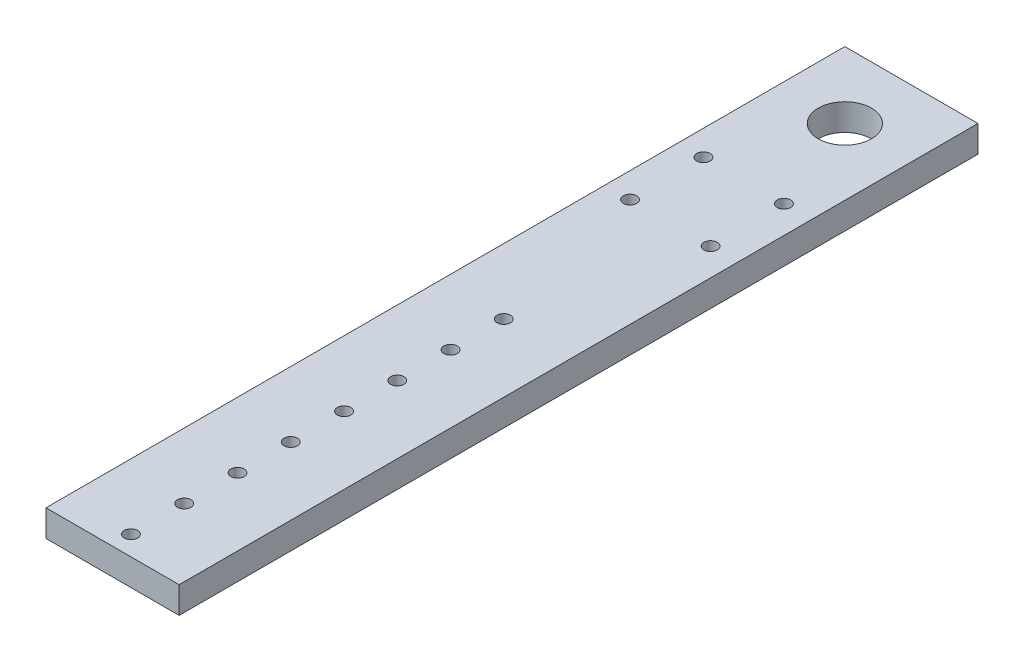
SolidWorks part; units mm, degrees
ref_plane "Front Plane" through (0, 0, 0) normal (0, 0, 1) x (1, 0, 0)
ref_plane "Top Plane" through (0, 0, 0) normal (0, 1, 0) x (1, 0, 0)
ref_plane "Right Plane" through (0, 0, 0) normal (1, 0, 0) x (0, 0, -1)
sketch "Sketch1" plane through (0, 0, 0) normal (0, 1, 0) x (1, 0, 0)
  line L1 (0, 0) -> (-127, 0)
  line L2 (0, 0) -> (0, 762)
  line L3 (0, 762) -> (-127, 762)
  line L4 (-127, 0) -> (-127, 762)
  point P7 (-52.4485, 452.4901)
  dimension "D1" = 762
  dimension "D2" = 127
extrude "Boss-Extrude1" add sketch "Sketch1" along normal blind 25.4 contours L3 L4 L1 L2
hole_wizard "1/2 (0.5) Diameter Hole1" positions "3DSketch1" profile "Sketch6" hole size "1/2" standard "ANSI Inch" end condition through all
sketch3d "3DSketch1"
  line L0 (0, 25.4, -762) -> (-127, 25.4, -762) construction
  line L1 (0, 25.4, 0) -> (0, 25.4, -762) construction
  point P0 (-63.5, 25.4, -698.5)
  dimension "D1" = 63.5
  dimension "D2" = 63.5
sketch "Sketch6" plane through (-63.5, 25.4, -698.5) normal (1, 0, 0) x (0, 0, 1)
  line L0 (0, 0) -> (0, 25.4)
  line L1 (0, 25.4) -> (25.4, 25.4)
  line L2 (25.4, 25.4) -> (25.4, 0)
  line L5 (25.4, 0) -> (0, 0)
  line L11 (0, -6.35) -> (0, 107.95) construction
  dimension "Thru Hole Dia." = 50.8
  dimension "Thru Hole Depth" = 25.4
hole_wizard "1/2 (0.5) Diameter Hole2" positions "Sketch9" profile "Sketch10" hole size "1/2" standard "ANSI Inch" end condition through all
sketch "Sketch9" plane through (0, 25.4, 0) normal (0, 1, 0) x (1, 0, 0)
  line L12 (-64.6204, 762) -> (-64.6204, 374.2885) construction
  line L13 (0, 762) -> (-127, 762) construction
  line L15 (-64.6204, 568.1443) -> (0, 568.1443) construction
  line L16 (0, 0) -> (0, 762) construction
  point P0 (-103.0261, 603.1311)
  point P40 (-64.6204, 374.2885)
  point P45 (-26.2148, 603.1311)
  point P52 (-26.2148, 533.1574)
  point P53 (-103.0261, 533.1574)
  point P61 (-64.6204, 323.4885)
  point P62 (-64.6204, 272.6885)
  point P63 (-64.6204, 221.8885)
  point P64 (-64.6204, 171.0885)
  point P65 (-64.6204, 120.2885)
  point P66 (-64.6204, 69.4885)
  point P67 (-64.6204, 18.6885)
  point P68 (-64.6204, -32.1115)
  dimension "D1" = 9
sketch "Sketch10" plane through (-103.0261, 25.4, -603.1311) normal (1, 0, 0) x (0, 0, 1)
  line L0 (0, 0) -> (0, 25.4)
  line L1 (0, 25.4) -> (6.35, 25.4)
  line L2 (6.35, 25.4) -> (6.35, 0)
  line L5 (6.35, 0) -> (0, 0)
  line L11 (0, -6.35) -> (0, 107.95) construction
  dimension "Thru Hole Dia." = 12.7
  dimension "Thru Hole Depth" = 25.4
